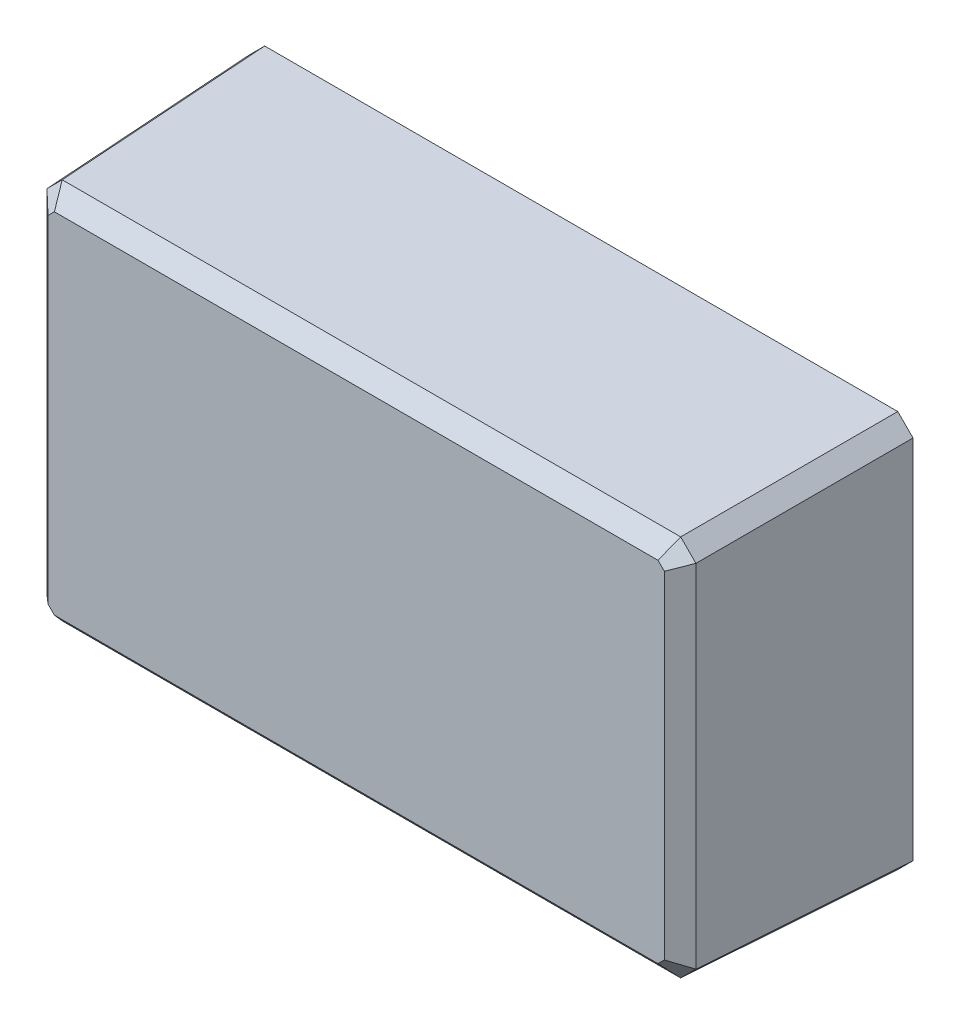
SolidWorks part; units mm, degrees
ref_plane "Front Plane" through (0, 0, 0) normal (0, 0, 1) x (1, 0, 0)
ref_plane "Top Plane" through (0, 0, 0) normal (0, 1, 0) x (1, 0, 0)
ref_plane "Right Plane" through (0, 0, 0) normal (1, 0, 0) x (0, 0, -1)
sketch "Sketch1" plane through (0, 0, 0) normal (0, 0, 1) x (1, 0, 0)
  line L1 (-43.5, 26) -> (43.5, 26)
  line L2 (-43.5, 26) -> (-43.5, -26)
  line L3 (-43.5, -26) -> (43.5, -26)
  line L4 (43.5, 26) -> (43.5, -26)
  line L5 (-43.5, 26) -> (43.5, -26) construction
  line L6 (-43.5, -26) -> (43.5, 26) construction
  point P0 (0, 0)
  dimension "D1" = 52
  dimension "D2" = 87
extrude "Boss-Extrude1" add sketch "Sketch1" along normal blind 29.5 draft 2
chamfer "Chamfer1" distance 2 angle 45 4 edges at (42.9849, -25.4849, 14.75) (42.9849, 25.4849, 14.75) (-42.9849, -25.4849, 14.75) (-42.9849, 25.4849, 14.75)
chamfer "Chamfer2" distance 2 angle 45 8 edges at (-41.4692, 23.968, 29.5) (-42.4698, -0.0012, 29.5) (-41.468, -23.9692, 29.5) (0.0012, -24.9698, 29.5) (41.4692, -23.968, 29.5) (42.4698, 0.0012, 29.5) (41.468, 23.9692, 29.5) (-0.0012, 24.9698, 29.5)
sketch "Sketch2" plane through (0, 0, 0) normal (0, 0, -1) x (-1, 0, 0)
  line L0 (-37.8, -14.75) -> (-37.8, -20.25) construction
  line L1 (38.2, 14.25) -> (38.2, 21) construction
  line L2 (-41.4963, 26) -> (41.4988, 26) construction
  line L3 (-43.5, -23.9963) -> (-43.5, 23.9988) construction
  circle A0 centre (38.2, 21) radius 0.5
  circle A1 centre (38.2, 14.25) radius 0.5
  circle A2 centre (-37.8, -14.75) radius 1
  circle A3 centre (-37.8, -20.25) radius 1
  dimension "D3" = 1
  dimension "D6" = 2
  dimension "D1" = 5
  dimension "D2" = 6.75
  dimension "D4" = 76
  dimension "D5" = 5.7
  dimension "D7" = 5.5
  dimension "D8" = 40.75
extrude "Boss-Extrude2" add sketch "Sketch2" along normal blind 3.5
